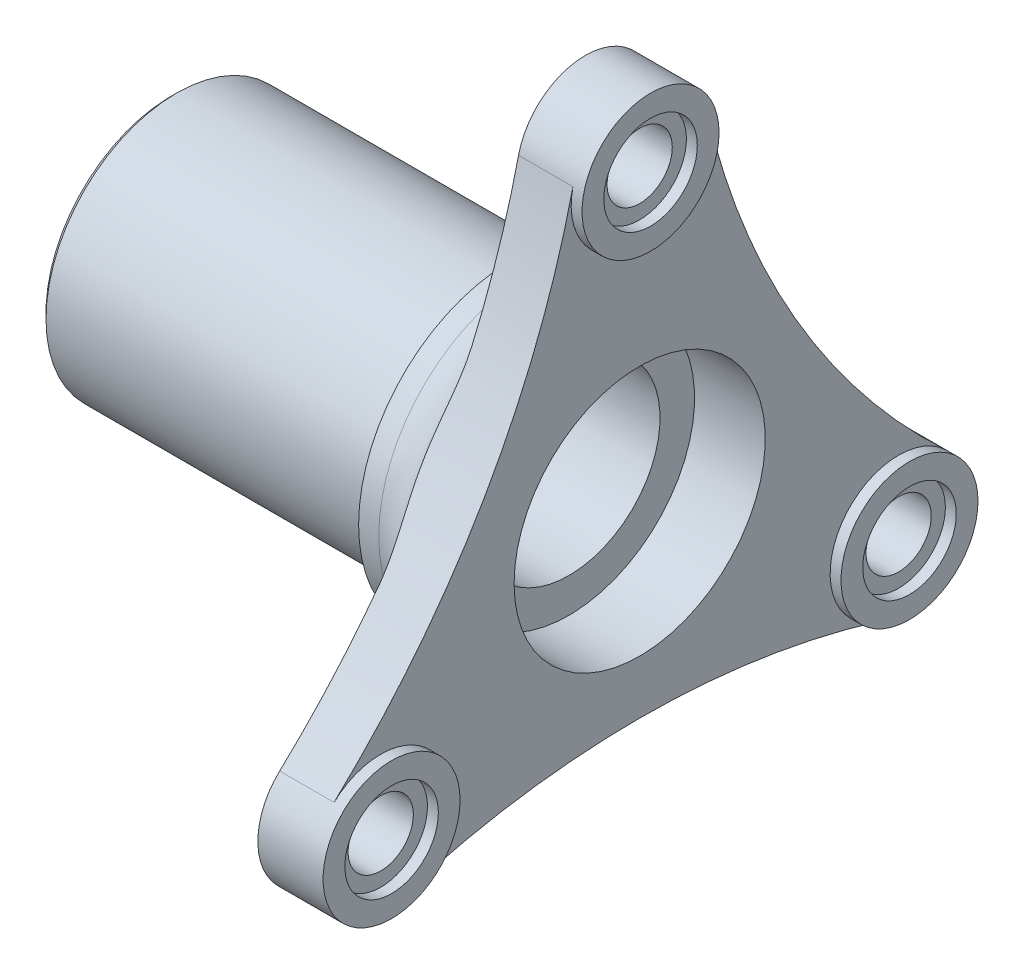
SolidWorks part; units mm, degrees
ref_plane "Front Plane" through (0, 0, 0) normal (0, 0, 1) x (1, 0, 0)
ref_plane "Top Plane" through (0, 0, 0) normal (0, 1, 0) x (1, 0, 0)
ref_plane "Right Plane" through (0, 0, 0) normal (1, 0, 0) x (0, 0, -1)
sketch "Sketch1" plane through (0, 0, 0) normal (0, 0, 1) x (1, 0, 0)
  line L0 (0, 0) -> (86.2, 0) construction
  line L1 (0, 24) -> (62.5, 24)
  line L2 (62.5, 24) -> (62.5, 28)
  line L3 (62.5, 28) -> (76.2, 28)
  line L4 (76.2, 28) -> (76.2, 67.6)
  line L5 (76.2, 67.6) -> (86.2, 67.6)
  line L6 (86.2, 67.6) -> (86.2, 23.1)
  line L7 (86.2, 23.1) -> (73.2, 23.1)
  line L8 (73.2, 23.1) -> (73.2, 16.75)
  line L9 (73.2, 16.75) -> (17.45, 16.75)
  line L10 (17.45, 16.75) -> (15.7, 18.5)
  line L11 (15.7, 18.5) -> (11.8, 18.5)
  line L12 (11.8, 18.5) -> (11.8, 20.6)
  line L13 (11.8, 20.6) -> (0, 20.6)
  line L14 (0, 20.6) -> (0, 24)
  point P10 (0, 0)
  point P18 (0, 22.3)
  point P19 (0, 0)
  dimension "D1" = 24
  dimension "D2" = 20.6
  dimension "D3" = 18.5
  dimension "D4" = 11.8
  dimension "D5" = 15.7
  dimension "D6" = 45
  dimension "D7" = 16.75
  dimension "D8" = 86.2
  dimension "D9" = 13
  dimension "D10" = 23.1
  dimension "D11" = 62.5
  dimension "D12" = 10
  dimension "D13" = 28
  dimension "D14" = 44.5
revolve "Revolve1" add sketch "Sketch1" angle 360 about L0
chamfer "Chamfer1" distance 1 angle 45 2 edges at (0, 0, 24) (0, 0, 20.6)
fillet "Fillet1" radius 10 1 edges at (76.2, 0, 28)
sketch "Sketch2" plane through (86.2, 0, 0) normal (1, 0, 0) x (0, 0, -1)
  circle A0 centre (0, 55) radius 6
  circle A1 centre (47.6314, -27.5) radius 6
  circle A2 centre (-47.6314, -27.5) radius 6
  circle A4 centre (0, 55) radius 12.6 construction
  circle A5 centre (47.6314, -27.5) radius 12.6 construction
  circle A6 centre (-47.6314, -27.5) radius 12.6 construction
  circle A7 centre (0, 0) radius 67.6 construction
  arc A8 (-56.2191, -18.2799) -> (-12.2787, 57.8271) centre (-158.4541, 91.4835) ccw
  arc A9 (12.2787, 57.8271) -> (56.2191, -18.2799) centre (158.4541, 91.4835) ccw
  arc A10 (43.9404, -39.5473) -> (-43.9404, -39.5473) centre (0, -182.9671) ccw
  arc A11 (-12.2787, 57.8271) -> (12.2787, 57.8271) centre (0, 55) cw
  arc A12 (56.2191, -18.2799) -> (43.9404, -39.5473) centre (47.6314, -27.5) cw
  arc A13 (-56.2191, -18.2799) -> (-43.9404, -39.5473) centre (-47.6314, -27.5) ccw
  circle A14 centre (0, 0) radius 70
  point P9 (0, 0)
  circle M7 centre (0, 0) radius 67.6
  dimension "D3" = 12
  dimension "D2" = 55
  dimension "D4" = 150
  dimension "D5" = 140
  dimension "D1" = 3
extrude "Cut-Extrude1" cut sketch "Sketch2" against normal blind 30 contours A13 A8 A11 M7 | A9 A12 A11 M7 | A13 A12 A10 M7 | A1 | A2 | A0
sketch "Sketch3" plane through (86.2, 0, 0) normal (1, 0, 0) x (0, 0, -1)
  circle A0 centre (0, 55) radius 12.6
  circle A1 centre (0, 55) radius 8.6
  circle A2 centre (47.6314, -27.5) radius 12.6
  circle A3 centre (47.6314, -27.5) radius 8.6
  circle A4 centre (-47.6314, -27.5) radius 12.6
  circle A5 centre (-47.6314, -27.5) radius 8.6
  arc A6 (-56.2191, -18.2799) -> (-43.9404, -39.5473) centre (-47.6314, -27.5) ccw construction
  arc A7 (43.9404, -39.5473) -> (56.2191, -18.2799) centre (47.6314, -27.5) ccw construction
  arc A8 (12.2787, 57.8271) -> (-12.2787, 57.8271) centre (0, 55) ccw construction
  dimension "D1" = 4
extrude "Boss-Extrude1" add sketch "Sketch3" along normal blind 2
